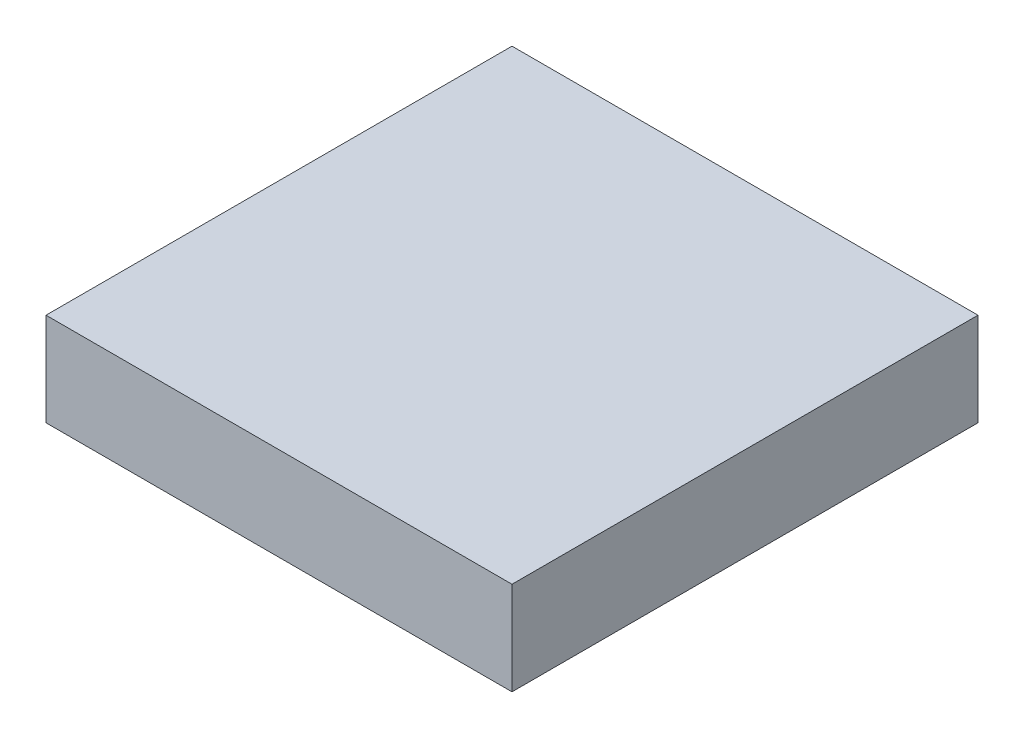
SolidWorks part; units mm, degrees
material "경질 폴리우레탄 폼"
ref_plane "정면" through (0, 0, 0) normal (0, 0, 1) x (1, 0, 0)
ref_plane "윗면" through (0, 0, 0) normal (0, 1, 0) x (1, 0, 0)
ref_plane "우측면" through (0, 0, 0) normal (1, 0, 0) x (0, 0, -1)
sketch "스케치1" plane through (0, 0, 0) normal (0, 1, 0) x (1, 0, 0)
  line L1 (-10, -10) -> (10, -10)
  line L2 (-10, -10) -> (-10, 10)
  line L3 (-10, 10) -> (10, 10)
  line L4 (10, -10) -> (10, 10)
  line L5 (-10, -10) -> (10, 10) construction
  line L6 (-10, 10) -> (10, -10) construction
  point P0 (0, 0)
  dimension "D1" = 20
  dimension "D2" = 20
extrude "보스-돌출1" add sketch "스케치1" along normal blind 4
